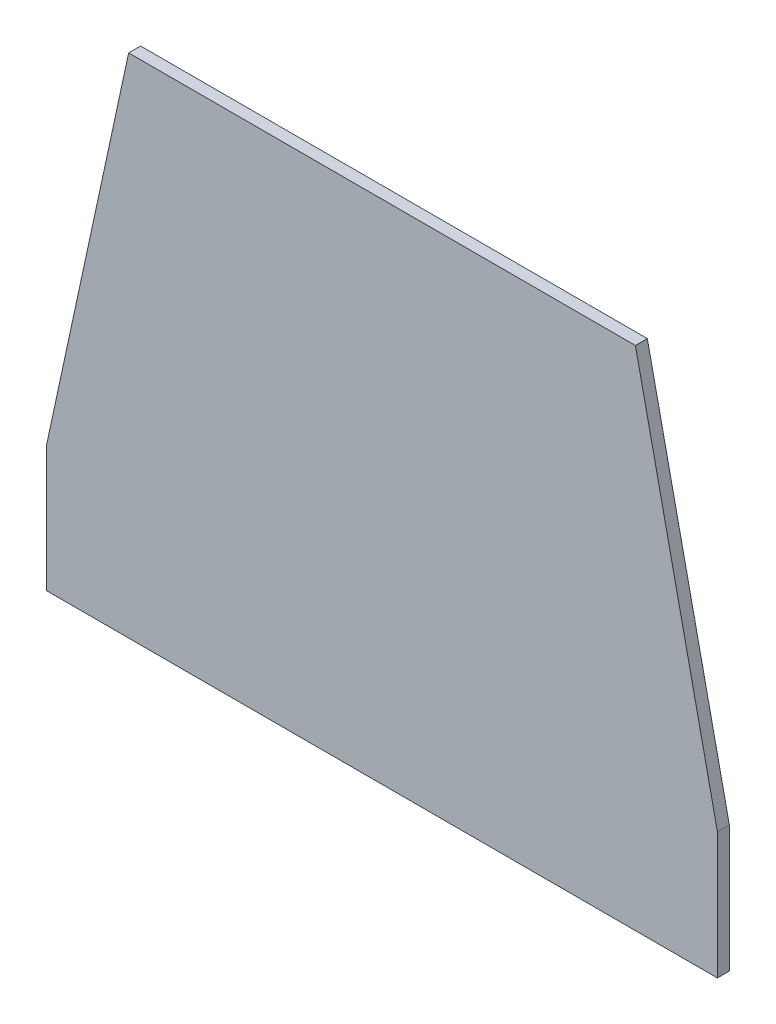
SolidWorks part; units mm, degrees
ref_plane "前视" through (0, 0, 0) normal (0, 0, 1) x (1, 0, 0)
ref_plane "上视" through (0, 0, 0) normal (0, 1, 0) x (1, 0, 0)
ref_plane "右视" through (0, 0, 0) normal (1, 0, 0) x (0, 0, -1)
sketch "草图2" plane through (0, 0, 0) normal (0, 0, 1) x (1, 0, 0)
  line L0 (110, 680) -> (0, 170)
  line L1 (0, 0) -> (900, 0)
  line L2 (0, 0) -> (0, 170)
  line L3 (110, 680) -> (790, 680)
  line L4 (900, 0) -> (900, 170)
  line L5 (450, 732.4608) -> (450, -110.1257) construction
  line L6 (790, 680) -> (900, 170)
  line L7 (110, 610) -> (938.0099, 610) construction
  line L8 (750, 870.5709) -> (750, 471.9627) construction
  line L9 (110, 310) -> (910, 310) construction
  line L10 (110, 530) -> (938.0099, 530) construction
  line L11 (450, 530) -> (944.1948, -87.8821) construction
  line L12 (603.3949, 164.813) -> (806.4775, 327.2426) construction
  line L13 (663.7287, 110.6282) -> (891.7517, 293.0057) construction
  line L14 (711.6834, 46.5423) -> (936.4569, 226.3208) construction
  line L15 (610.0301, 201.8375) -> (761.264, 12.7528) construction
  line L16 (733.9352, 303.0814) -> (876.4232, 124.9314) construction
  line L17 (506, 262.1445) -> (506, 27.5399) construction
  point P5 (0, 170)
  point P6 (110, 680)
  point P15 (450, 50)
  dimension "D7" = 50
  dimension "D1" = 900
  dimension "D2" = 680
  dimension "D3" = 170
  dimension "D4" = 110
  dimension "D5" = 70
  dimension "D6" = 40
  dimension "D12" = 56
  dimension "D14" = 300
  dimension "D18" = 80
  dimension "D19" = 38.654
  dimension "D20" = 381
  dimension "D22" = 80
  dimension "D23" = 80
  dimension "D24" = 80
  dimension "D25" = 80
extrude "基体-拉伸" add sketch "草图2" along normal blind 16
